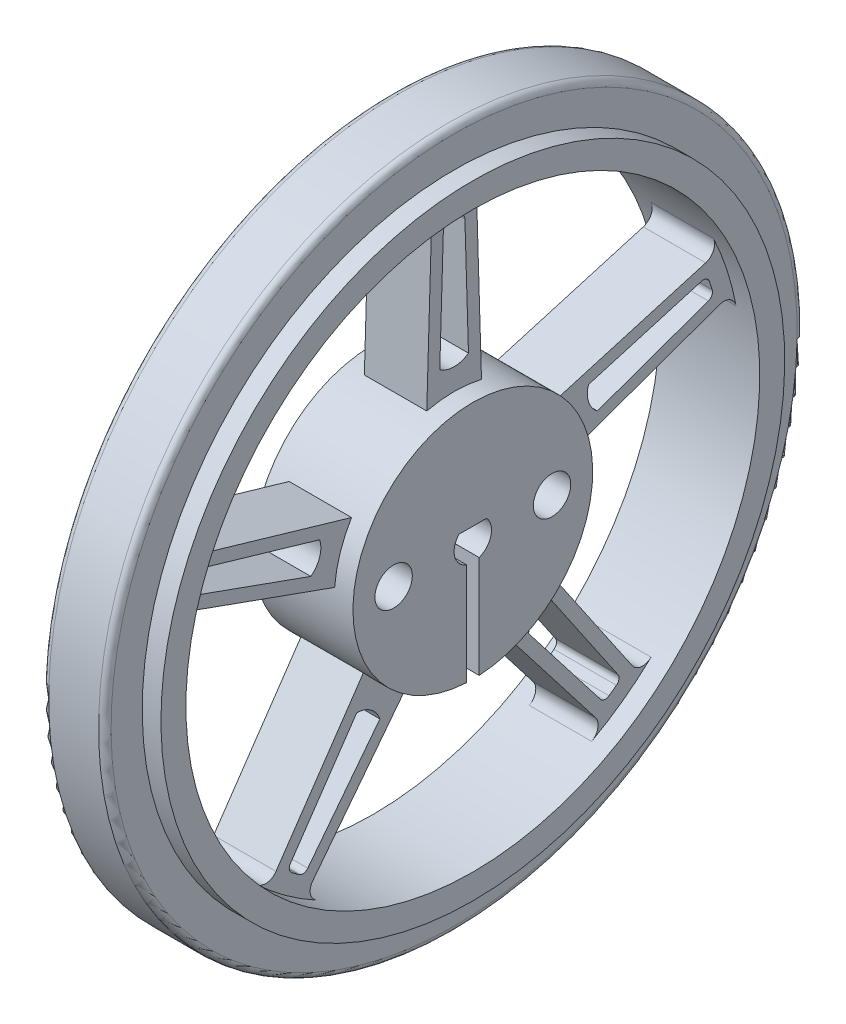
SolidWorks part; units mm, degrees
ref_plane "Front Plane" through (0, 0, 0) normal (0, 0, 1) x (1, 0, 0)
ref_plane "Top Plane" through (0, 0, 0) normal (0, 1, 0) x (1, 0, 0)
ref_plane "Right Plane" through (0, 0, 0) normal (1, 0, 0) x (0, 0, -1)
sketch "Sketch2" plane through (0, 0, 0) normal (0, 0, 1) x (1, 0, 0)
  line L0 (0, 23) -> (0, -23) construction
  line L1 (-65.5279, 0) -> (65.5279, 0) construction
  line L2 (-4, -25) -> (-4, -23)
  line L3 (-4, -25) -> (4, -25)
  line L4 (-4, -23) -> (4, -23)
  line L5 (4, -25) -> (4, -23)
  line L6 (-4, -25) -> (4, -23) construction
  line L7 (-4, -23) -> (4, -25) construction
  line L8 (-2.5, -25) -> (-2.5, -27.5)
  line L9 (-2, -28) -> (2, -28)
  line L10 (2.5, -25) -> (2.5, -27.5)
  arc A0 (2.5, -27.5) -> (2, -28) centre (2, -27.5) cw
  arc A1 (-2.5, -27.5) -> (-2, -28) centre (-2, -27.5) ccw
  point P6 (0, -24)
  point P15 (0, -28)
  point P17 (2.5, -28)
  point P20 (-2.5, -28)
  dimension "D6" = 0.5
  dimension "D1" = 5
  dimension "D2" = 8
  dimension "D3" = 2
  dimension "D4" = 3
  dimension "D5" = 28
revolve "Revolve1" add sketch "Sketch2" angle 360 mid plane about L1
sketch "Sketch3" plane through (-2.5, 0, 0) normal (-1, 0, 0) x (0, 0, 1)
  line L0 (0, 33.6718) -> (0, -6.0452) construction
  line L1 (0, 0) -> (6.35, 0) construction
  line L2 (-1.1095, 1.0095) -> (1.1095, 1.0095)
  line L3 (-0.5058, -1.4121) -> (0.5058, -1.4121) construction
  line L4 (-0.5058, -9.598) -> (-0.5058, -1.4121)
  line L6 (0.5058, -9.598) -> (0.5058, -1.4121)
  arc A0 (0.5058, -9.598) -> (-0.5058, -9.598) centre (0, 0) ccw
  circle A1 centre (6.35, 0) radius 1.5
  circle A2 centre (-6.35, 0) radius 1.5
  arc A3 (-1.1095, 1.0095) -> (-0.5058, -1.4121) centre (0, 0) ccw
  arc A4 (0.5058, -1.4121) -> (1.1095, 1.0095) centre (0, 0) ccw
  dimension "D2" = 3
  dimension "D1" = 12.7
extrude "Boss-Extrude1" add sketch "Sketch3" against normal up to surface and the other way up to surface separate body up to face at (4, -23, 0) other way up to face at (-4, -23, 0)
sketch "Sketch4" plane through (-2.5, 0, 0) normal (-1, 0, 0) x (0, 0, 1)
  line L0 (0, 23) -> (0, 0) construction
  line L1 (-2.1938, 9.3576) -> (-1.7837, 22.9307)
  line L2 (2.1938, 9.3576) -> (1.7837, 22.9307)
  line L3 (-0.809, 22.9858) -> (-1.2155, 9.5341) construction
  line L4 (0.809, 22.9858) -> (1.2155, 9.5341) construction
  line L5 (-0.3649, 21.6301) -> (0.3649, 21.6301)
  line L6 (-1.15, 11.7021) -> (1.15, 11.7021) construction
  line L7 (-0.8647, 21.1452) -> (-1.15, 11.7021)
  line L8 (0.8647, 21.1452) -> (1.15, 11.7021)
  line L9 (-0.85, 21.6301) -> (0.85, 21.6301) construction
  line L10 (-0.809, 22.9858) -> (0.809, 22.9858) construction
  arc A0 (0.5058, -9.598) -> (-0.5058, -9.598) centre (0, 0) ccw construction
  arc A1 (2.1938, 9.3576) -> (-2.1938, 9.3576) centre (0, 0) ccw
  arc A2 (0.3649, 21.6301) -> (0.8647, 21.1452) centre (0.3649, 21.1301) cw
  arc A3 (-0.3649, 21.6301) -> (-0.8647, 21.1452) centre (-0.3649, 21.1301) ccw
  arc A4 (-1.15, 11.7021) -> (1.15, 11.7021) centre (0, 13.3048) ccw
  circle A5 centre (0, 0) radius 23 construction
  arc A6 (1.7837, 22.9307) -> (-1.7837, 22.9307) centre (0, 0) ccw
  point P22 (0.85, 21.6301)
  point P25 (-0.85, 21.6301)
  dimension "D1" = 0.5
  dimension "D2" = 1.7
  dimension "D3" = 2.3
extrude "Boss-Extrude2" add sketch "Sketch4" against normal up to surface (5 mm away) contours L2 A6 L1 A1 A4 L7 A3 L5 A2 L8 up to face at (2.5, -27.5, 0)
fillet "Fillet1" radius 1 1 edges at (0, 22.9307, 1.7837)
fillet "Fillet2" radius 1 1 edges at (0, 22.9307, -1.7837)
pattern_circular "CirPattern1" count 5 over 360 about axis through (0, 0, 0) along (1, 0, 0) of "Boss-Extrude2", "Fillet2", "Fillet1"
sketch "Sketch5" plane through (-4, 0, 0) normal (-1, 0, 0) x (0, 0, 1)
  line L0 (1.1095, 1.0095) -> (-1.1095, 1.0095) construction
  line L1 (0.5058, -9.598) -> (0.5058, -1.4121) construction
  line L2 (-0.5058, -1.4121) -> (-0.5058, -9.598) construction
  line L3 (1.1095, 1.0095) -> (-1.1095, 1.0095)
  line L4 (0.5058, -9.598) -> (0.5058, -1.4121)
  line L5 (-0.5058, -1.4121) -> (-0.5058, -9.598)
  arc A0 (0.5058, -3.4633) -> (-0.5058, -3.4633) centre (0, 0) ccw
  arc A1 (-1.1095, 1.0095) -> (-0.5058, -1.4121) centre (0, 0) ccw construction
  arc A2 (0.5058, -1.4121) -> (1.1095, 1.0095) centre (0, 0) ccw construction
  arc A3 (-1.1095, 1.0095) -> (-0.5058, -1.4121) centre (0, 0) ccw
  arc A4 (0.5058, -1.4121) -> (1.1095, 1.0095) centre (0, 0) ccw
  line M3 (-1.1095, 1.0095) -> (1.1095, 1.0095)
  arc M4 (1.1095, 1.0095) -> (0.5058, -1.4121) centre (0, 0) cw
  line M5 (0.5058, -1.4121) -> (0.5058, -9.598)
  arc M8 (-0.5058, -1.4121) -> (-1.1095, 1.0095) centre (0, 0) cw
  dimension "D1" = 3.5
extrude "Boss-Extrude3" add sketch "Sketch5" along normal blind 3 contours A0 L5 M5 M8 M3 M4
fillet "Fillet3" radius 0.5 1 edges at (-7, 3.5, 0)
